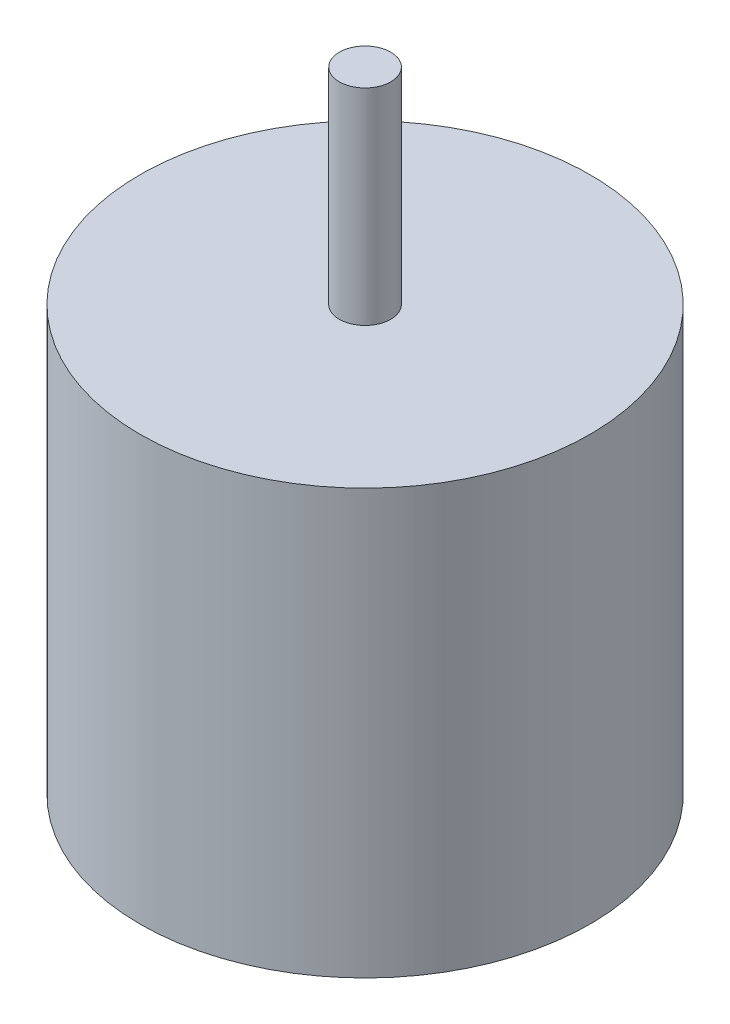
SolidWorks part; units mm, degrees
ref_plane "Front Plane" through (0, 0, 0) normal (0, 0, 1) x (1, 0, 0)
ref_plane "Top Plane" through (0, 0, 0) normal (0, 1, 0) x (1, 0, 0)
ref_plane "Right Plane" through (0, 0, 0) normal (1, 0, 0) x (0, 0, -1)
sketch "Sketch1" plane through (0, 0, 0) normal (0, 1, 0) x (1, 0, 0)
  circle A0 centre (0, 0) radius 17.5
  dimension "D1" = 35
extrude "Boss-Extrude1" add sketch "Sketch1" along normal blind 33
sketch "Sketch2" plane through (0, 33, 0) normal (0, 1, 0) x (1, 0, 0)
  circle A0 centre (0, 0) radius 2
  dimension "D1" = 4
extrude "Boss-Extrude2" add sketch "Sketch2" along normal blind 16
